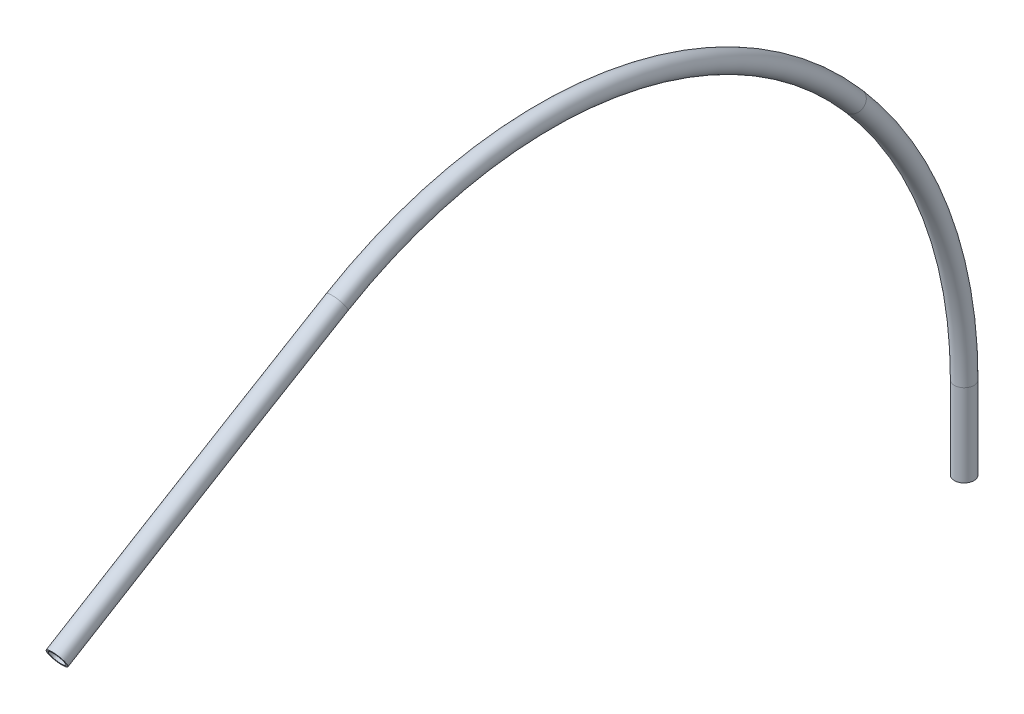
SolidWorks part; units mm, degrees
ref_plane "Alzado" through (0, 0, 0) normal (0, 0, 1) x (1, 0, 0)
ref_plane "Planta" through (0, 0, 0) normal (0, 1, 0) x (1, 0, 0)
ref_plane "Vista lateral" through (0, 0, 0) normal (1, 0, 0) x (0, 0, -1)
sketch "Croquis5" plane through (0, 0, 0) normal (1, 0, 0) x (0, 0, -1)
  line L0 (-12, 40) -> (-12, 82.2054)
  arc A0 (-12, 82.2054) -> (-68.3541, 233.8403) centre (-244.183, 82.2054) ccw
  arc A1 (-68.3541, 233.8403) -> (-332.9206, 277.0647) centre (-226.4425, 97.5048) ccw
  arc A2 (-332.9206, 277.0647) -> (-476.2262, 190.8469) centre (6364.2347, -11016.7175) ccw
  dimension "D1" = 40
ref_plane "Plano1" through (0, 40, 12) normal (0, 1, 0) x (-1, 0, 0)
sketch "Croquis7" plane through (0, 40, 12) normal (0, 1, 0) x (-1, 0, 0)
  circle A0 centre (0, 0) radius 5
  dimension "D1" = 10
sweep "Barrer1" add profiles "Croquis7" path "Croquis5"
shell "Vaciado2" thickness 1
